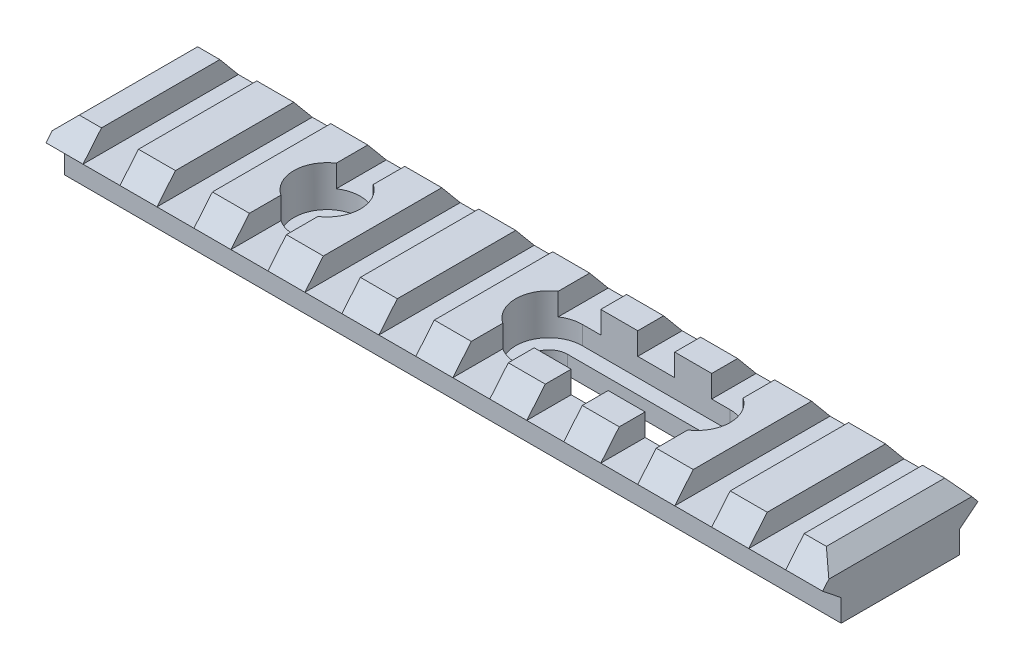
SolidWorks part; units mm, degrees
ref_plane "前视基准面" through (0, 0, 0) normal (0, 0, 1) x (1, 0, 0)
ref_plane "上视基准面" through (0, 0, 0) normal (0, 1, 0) x (1, 0, 0)
ref_plane "右视基准面" through (0, 0, 0) normal (1, 0, 0) x (0, 0, -1)
other "Configuration Table"
sketch "草图1" plane through (0, 0, 0) normal (1, 0, 0) x (0, 0, -1)
  line L6 (-8, 0) -> (8, 0)
  line L7 (8, 0) -> (8, 3)
  line L8 (8, 3) -> (10.5, 5)
  line L9 (10.5, 5) -> (8, 8)
  line L10 (8, 8) -> (-8, 8)
  line L11 (-8, 8) -> (-10.5, 5)
  line L12 (-10.5, 5) -> (-8, 3)
  line L13 (-8, 3) -> (-8, 0)
  line L14 (0, 0) -> (0, 8) construction
  dimension "D1" = 16
  dimension "D2" = 16
  dimension "D3" = 21
  dimension "D4" = 5
  dimension "D5" = 8
  dimension "D6" = 3
extrude "凸台-拉伸1" add sketch "草图1" along normal mid plane 105
sketch "草图2" plane through (0, 8, 0) normal (0, 1, 0) x (1, 0, 0)
  line L0 (0, 8) -> (0, -8) construction
  line L1 (52.5, 8) -> (-52.5, 8) construction
  line L2 (52.5, -8) -> (-52.5, -8) construction
  line L3 (52.5, 10.5) -> (-52.5, 10.5) construction
  line L4 (-7.5, -10.5) -> (-2.5, -10.5)
  line L5 (-7.5, -10.5) -> (-7.5, 10.5)
  line L6 (-7.5, 10.5) -> (-2.5, 10.5)
  line L7 (-2.5, -10.5) -> (-2.5, 10.5)
  line L8 (47.5, -10.5) -> (42.5, -10.5)
  line L9 (42.5, -10.5) -> (42.5, 10.5)
  line L10 (52.5, -10.5) -> (-52.5, -10.5) construction
  line L11 (-17.5, -10.5) -> (-17.5, 10.5)
  line L12 (-17.5, 10.5) -> (-12.5, 10.5)
  line L13 (-12.5, -10.5) -> (-12.5, 10.5)
  line L14 (-17.5, -10.5) -> (-12.5, -10.5)
  line L15 (-27.5, -10.5) -> (-27.5, 10.5)
  line L16 (-27.5, 10.5) -> (-22.5, 10.5)
  line L17 (-22.5, -10.5) -> (-22.5, 10.5)
  line L18 (-27.5, -10.5) -> (-22.5, -10.5)
  line L19 (-37.5, -10.5) -> (-37.5, 10.5)
  line L20 (-37.5, 10.5) -> (-32.5, 10.5)
  line L21 (-32.5, -10.5) -> (-32.5, 10.5)
  line L22 (-37.5, -10.5) -> (-32.5, -10.5)
  line L23 (-47.5, -10.5) -> (-47.5, 10.5)
  line L24 (-47.5, 10.5) -> (-42.5, 10.5)
  line L25 (-42.5, -10.5) -> (-42.5, 10.5)
  line L26 (-47.5, -10.5) -> (-42.5, -10.5)
  line L27 (47.5, 10.5) -> (42.5, 10.5)
  line L28 (47.5, -10.5) -> (47.5, 10.5)
  line L29 (37.5, -10.5) -> (32.5, -10.5)
  line L30 (32.5, -10.5) -> (32.5, 10.5)
  line L31 (37.5, 10.5) -> (32.5, 10.5)
  line L32 (37.5, -10.5) -> (37.5, 10.5)
  line L33 (27.5, -10.5) -> (22.5, -10.5)
  line L34 (22.5, -10.5) -> (22.5, 10.5)
  line L35 (27.5, 10.5) -> (22.5, 10.5)
  line L36 (27.5, -10.5) -> (27.5, 10.5)
  line L37 (17.5, -10.5) -> (12.5, -10.5)
  line L38 (12.5, -10.5) -> (12.5, 10.5)
  line L39 (17.5, 10.5) -> (12.5, 10.5)
  line L40 (17.5, -10.5) -> (17.5, 10.5)
  line L41 (2.5, -10.5) -> (2.5, 10.5)
  line L42 (7.5, 10.5) -> (2.5, 10.5)
  line L43 (7.5, -10.5) -> (7.5, 10.5)
  line L44 (7.5, -10.5) -> (2.5, -10.5)
  dimension "D1" = 5
  dimension "D2" = 5
  dimension "D4" = 5
  dimension "D3" = 5
extrude "切除-拉伸1" cut sketch "草图2" against normal up to vertex (3 mm away) up to point (-52.5, 5, 10.5)
sketch "草图3" plane through (0, 0, 0) normal (0, -1, 0) x (1, 0, 0)
  line L0 (5, 0) -> (25, 0) construction
  line L1 (5, 2.5) -> (25, 2.5)
  line L2 (5, -2.5) -> (25, -2.5)
  line L3 (52.5, 8) -> (52.5, -8) construction
  line L4 (-52.5, 8) -> (-52.5, -8) construction
  arc A0 (5, 2.5) -> (5, -2.5) centre (5, 0) ccw
  arc A1 (25, -2.5) -> (25, 2.5) centre (25, 0) ccw
  circle A2 centre (-25, 0) radius 2.5
  point P3 (15, 0)
  dimension "D1" = 5
  dimension "D2" = 2.5
  dimension "D3" = 30
  dimension "D4" = 27.5
  dimension "D5" = 27.5
extrude "切除-拉伸2" cut sketch "草图3" against normal through all both and the other way through all
sketch "草图4" plane through (0, 0, 0) normal (0, 0, 1) x (1, 0, 0)
  line L0 (-52.5, 6) -> (-50.5, 8)
  line L1 (-52.5, 8) -> (-52.5, 5) construction
  line L2 (-47.5, 8) -> (-52.5, 8) construction
  line L3 (-50.5, 8) -> (-52.5, 8)
  line L4 (-52.5, 8) -> (-52.5, 6)
  dimension "D1" = 1
  dimension "D2" = 3
extrude "切除-拉伸3" cut sketch "草图4" against normal through all both and the other way through all
mirror "镜向1" about plane through (0, 0, 0) normal (1, 0, 0) of "切除-拉伸3"
sketch "草图5" plane through (0, 8, 0) normal (0, 1, 0) x (1, 0, 0)
  line L0 (7.5, -2.5) -> (5, -2.5) construction
  line L1 (12.5, -2.5) -> (7.5, -2.5) construction
  line L2 (12.5, -2.5) -> (17.5, -2.5) construction
  line L3 (22.5, -2.5) -> (17.5, -2.5) construction
  line L4 (22.5, -2.5) -> (25, -2.5) construction
  line L5 (25, 2.5) -> (22.5, 2.5) construction
  line L6 (17.5, 2.5) -> (22.5, 2.5) construction
  line L7 (17.5, 2.5) -> (12.5, 2.5) construction
  line L8 (7.5, 2.5) -> (12.5, 2.5) construction
  line L9 (5, 2.5) -> (7.5, 2.5) construction
  line L10 (7.5, -2.5) -> (5, -2.5)
  line L11 (12.5, -2.5) -> (7.5, -2.5)
  line L12 (12.5, -2.5) -> (17.5, -2.5)
  line L13 (22.5, -2.5) -> (17.5, -2.5)
  line L14 (22.5, -2.5) -> (25, -2.5)
  line L15 (25, 2.5) -> (22.5, 2.5)
  line L16 (17.5, 2.5) -> (22.5, 2.5)
  line L17 (17.5, 2.5) -> (12.5, 2.5)
  line L18 (7.5, 2.5) -> (12.5, 2.5)
  line L19 (5, 2.5) -> (7.5, 2.5)
  line L20 (5, 0) -> (25, 0) construction
  line L21 (5, 4.5) -> (25, 4.5)
  line L22 (5, -4.5) -> (25, -4.5)
  arc A0 (5, 2.5) -> (2.5, 0) centre (5, 0) ccw construction
  arc A1 (2.5, 0) -> (5, -2.5) centre (5, 0) ccw construction
  arc A2 (25, -2.5) -> (27.5, 0) centre (25, 0) ccw construction
  arc A3 (27.5, 0) -> (25, 2.5) centre (25, 0) ccw construction
  arc A4 (5, 2.5) -> (2.5, 0) centre (5, 0) ccw
  arc A5 (2.5, 0) -> (5, -2.5) centre (5, 0) ccw
  arc A6 (25, -2.5) -> (27.5, 0) centre (25, 0) ccw
  arc A7 (27.5, 0) -> (25, 2.5) centre (25, 0) ccw
  arc A8 (5, 4.5) -> (5, -4.5) centre (5, 0) ccw
  arc A9 (25, -4.5) -> (25, 4.5) centre (25, 0) ccw
  circle A10 centre (-25, 0) radius 4.5
  point P4 (15, 0)
  dimension "D1" = 4.5
  dimension "D2" = 9
extrude "切除-拉伸4" cut sketch "草图5" against normal offset from surface (5.5 mm away) 2.5 up to face at (15, 0, 0)
